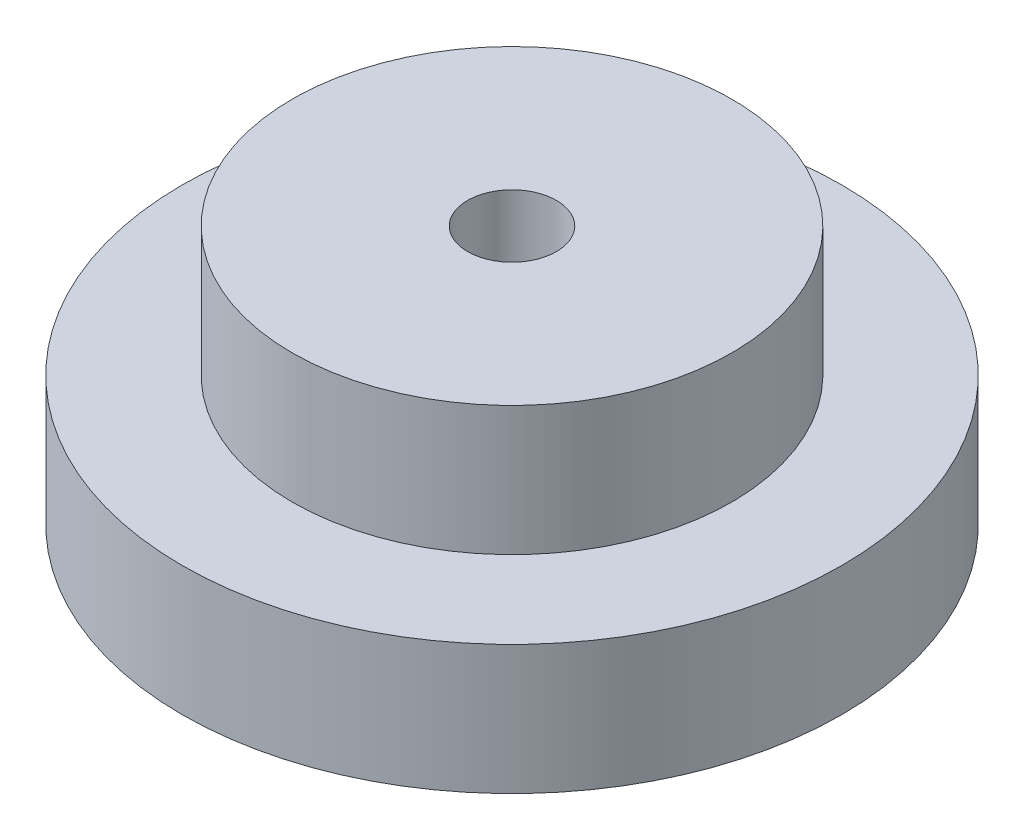
SolidWorks part; units mm, degrees
ref_plane "Front Plane" through (0, 0, 0) normal (0, 0, 1) x (1, 0, 0)
ref_plane "Top Plane" through (0, 0, 0) normal (0, 1, 0) x (1, 0, 0)
ref_plane "Right Plane" through (0, 0, 0) normal (1, 0, 0) x (0, 0, -1)
sketch "Sketch1" plane through (0, 0, 0) normal (0, 1, 0) x (1, 0, 0)
  circle A0 centre (0, 0) radius 14.85
  circle A1 centre (0, 0) radius 2
  dimension "D1" = 29.7
  dimension "D2" = 4
extrude "Boss-Extrude1" add sketch "Sketch1" along normal blind 5.82
sketch "Sketch2" plane through (0, 5.82, 0) normal (0, 1, 0) x (1, 0, 0)
  circle A0 centre (0, 0) radius 2
  circle A1 centre (0, 0) radius 2 construction
  circle A2 centre (0, 0) radius 9.9
  dimension "D1" = 19.8
extrude "Boss-Extrude2" add sketch "Sketch2" along normal blind 5.82
